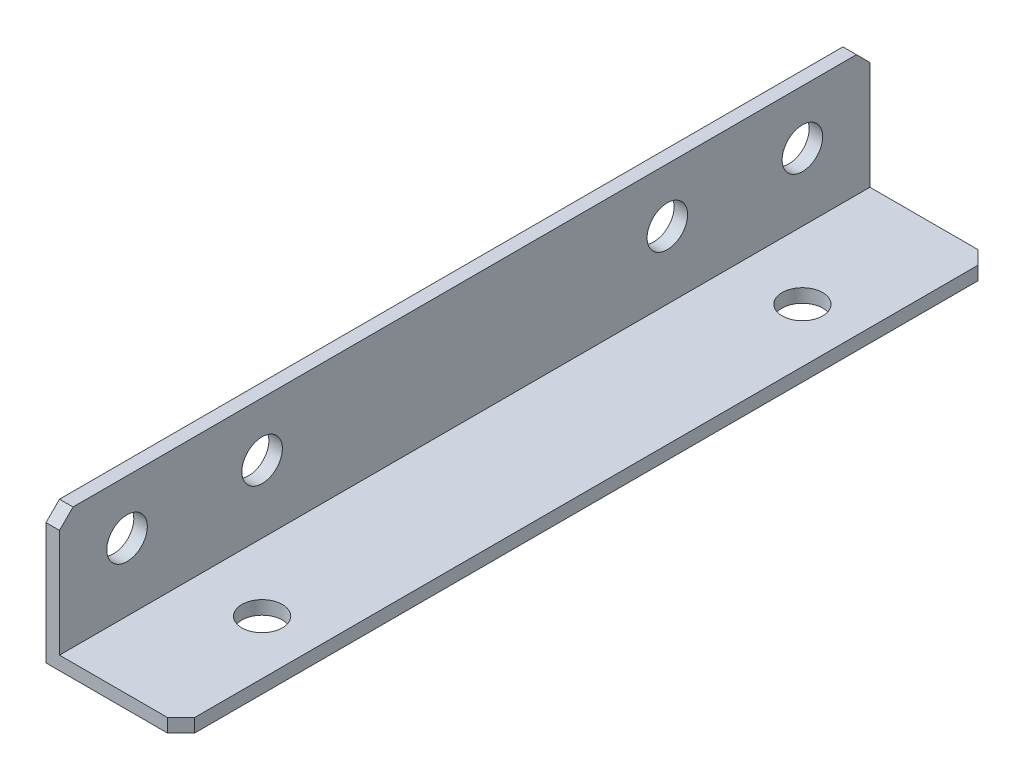
SolidWorks part; units mm, degrees
ref_plane "Ebene vorne" through (0, 0, 0) normal (0, 0, 1) x (1, 0, 0)
ref_plane "Ebene oben" through (0, 0, 0) normal (0, 1, 0) x (1, 0, 0)
ref_plane "Ebene rechts" through (0, 0, 0) normal (1, 0, 0) x (0, 0, -1)
sketch "Skizze1" plane through (0, 0, 0) normal (0, 0, 1) x (1, 0, 0)
  line L0 (0, 10) -> (0, 0)
  line L1 (0, 0) -> (10, 0)
  dimension "D1" = 10
extrude "Linear-Austragen-Dünn1" add sketch "Skizze1" along normal mid plane 60 thin thin type one direction reverse wall 1
chamfer "Fase1" distance 1 angle 45 4 edges at (0.5, 10, -30) (10, 0.5, -30) (10, 0.5, 30) (0.5, 10, 30)
sketch "Skizze2" plane through (1, 0, 0) normal (1, 0, 0) x (0, 0, -1)
  line L0 (-15, 6) -> (15, 6) construction
  line L1 (-29, 10) -> (29, 10) construction
  line L2 (-30, 9) -> (-30, 1) construction
  line L3 (30, 9) -> (30, 1) construction
  circle A0 centre (-15, 6) radius 1.5
  circle A1 centre (15, 6) radius 1.5
  circle A2 centre (-25, 6) radius 1.5
  circle A3 centre (25, 6) radius 1.5
  point P2 (0, 6)
  dimension "D3" = 3
  dimension "D1" = 30
  dimension "D2" = 4
  dimension "D4" = 5
  dimension "D5" = 5
extrude "Schnitt-Linear austragen1" cut sketch "Skizze2" against normal blind 10
sketch "Skizze3" plane through (0, 1, 0) normal (0, 1, 0) x (1, 0, 0)
  line L0 (6, -20) -> (6, 20) construction
  line L1 (10, -29) -> (10, 29) construction
  circle A0 centre (6, -20) radius 1.5
  circle A1 centre (6, 20) radius 1.5
  point P2 (6, 0)
  dimension "D3" = 3
  dimension "D1" = 40
  dimension "D2" = 4
extrude "Schnitt-Linear austragen2" cut sketch "Skizze3" against normal blind 10
sketch "Skizze4" [suppressed] plane through (0, 1, 0) normal (0, 1, 0) x (1, 0, 0)
  line L0 (6, -20) -> (6, 20) construction
  circle A0 centre (6, 0) radius 3
  dimension "D1" = 6
extrude "Schnitt-Linear austragen3" [suppressed] cut sketch "Skizze4" against normal blind 10
